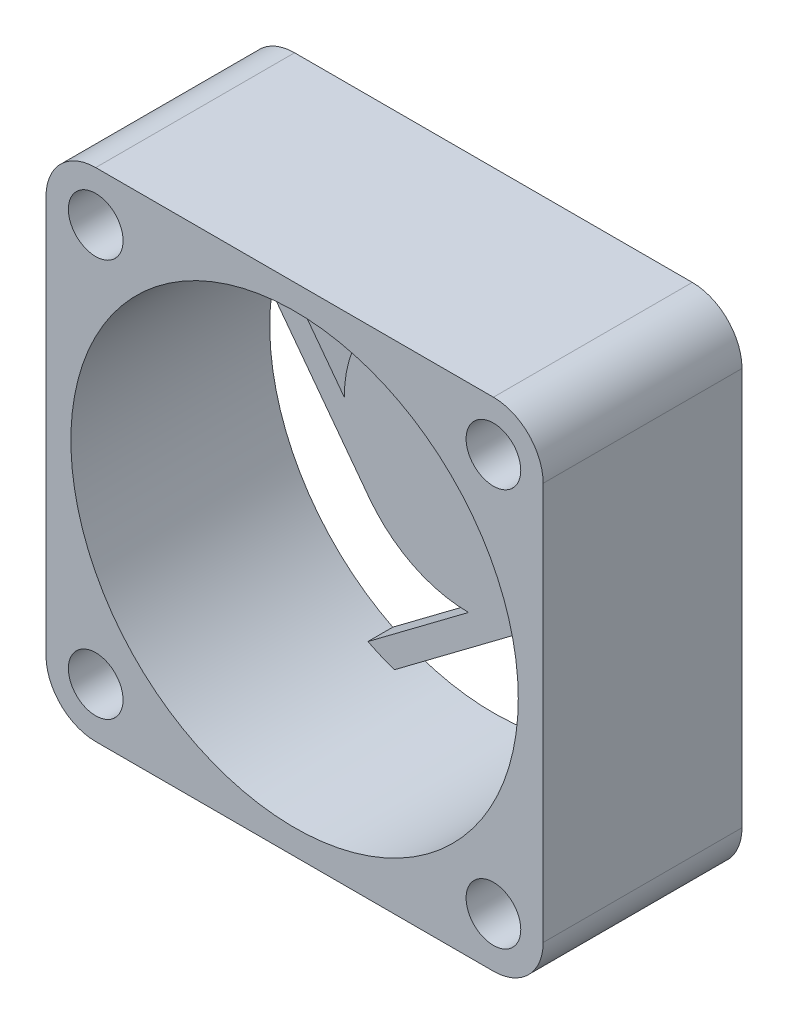
SolidWorks part; units mm, degrees
ref_plane "Front Plane" through (0, 0, 0) normal (0, 0, 1) x (1, 0, 0)
ref_plane "Top Plane" through (0, 0, 0) normal (0, 1, 0) x (1, 0, 0)
ref_plane "Right Plane" through (0, 0, 0) normal (1, 0, 0) x (0, 0, -1)
sketch "Sketch1" plane through (0, 0, 0) normal (0, 0, 1) x (1, 0, 0)
  line L1 (-10, -10) -> (10, -10)
  line L2 (-10, -10) -> (-10, 10)
  line L3 (-10, 10) -> (10, 10)
  line L4 (10, -10) -> (10, 10)
  line L5 (-10, -10) -> (10, 10) construction
  line L6 (-10, 10) -> (10, -10) construction
  circle A0 centre (-8, 8) radius 1.1
  circle A1 centre (-8, -8) radius 1.1
  circle A2 centre (8, -8) radius 1.1
  circle A3 centre (8, 8) radius 1.1
  point P0 (0, 0)
  dimension "D3" = 2.2
  dimension "D1" = 20
  dimension "D2" = 20
  dimension "D4" = 8
  dimension "D5" = 2
  dimension "D6" = 2
extrude "Boss-Extrude1" add sketch "Sketch1" along normal blind 8
sketch "Sketch2" plane through (0, 0, 8) normal (0, 0, 1) x (1, 0, 0)
  circle A0 centre (0, 0) radius 9
  dimension "D1" = 18
extrude "Cut-Extrude1" cut sketch "Sketch2" against normal blind 7
sketch "Sketch3" plane through (0, 0, 1) normal (0, 0, 1) x (1, 0, 0)
  line L0 (3, -4) -> (-2.9867, -8.49)
  line L1 (0, -5) -> (-4.0498, -8.0374)
  line L2 (-5, 0) -> (-8.0374, 4.0498)
  line L3 (-4, -3) -> (-8.49, 2.9867)
  line L4 (0, 5) -> (4.0498, 8.0374)
  line L5 (-3, 4) -> (2.9867, 8.49)
  line L6 (5, 0) -> (8.0374, -4.0498)
  line L7 (4, 3) -> (8.49, -2.9867)
  arc A0 (-8.49, 2.9867) -> (-4.0498, -8.0374) centre (0, 0) ccw
  arc A1 (-4, -3) -> (0, -5) centre (0, 0) ccw
  arc A2 (-8.0374, 4.0498) -> (-8.49, 2.9867) centre (0, 0) ccw construction
  arc A3 (-5, 0) -> (-4, -3) centre (0, 0) ccw construction
  arc A4 (0, 5) -> (-3, 4) centre (0, 0) ccw construction
  arc A5 (-3, 4) -> (-5, 0) centre (0, 0) ccw
  arc A6 (5, 0) -> (4, 3) centre (0, 0) ccw construction
  arc A7 (4, 3) -> (0, 5) centre (0, 0) ccw
  arc A8 (0, -5) -> (3, -4) centre (0, 0) ccw construction
  arc A9 (3, -4) -> (5, 0) centre (0, 0) ccw
  arc A10 (-4.0498, -8.0374) -> (-2.9867, -8.49) centre (0, 0) ccw construction
  arc A11 (-2.9867, -8.49) -> (8.0374, -4.0498) centre (0, 0) ccw
  arc A12 (8.0374, -4.0498) -> (8.49, -2.9867) centre (0, 0) ccw construction
  arc A13 (8.49, -2.9867) -> (4.0498, 8.0374) centre (0, 0) ccw
  arc A14 (4.0498, 8.0374) -> (2.9867, 8.49) centre (0, 0) ccw construction
  arc A15 (2.9867, 8.49) -> (-8.0374, 4.0498) centre (0, 0) ccw
  point P23 (0, 0)
  dimension "D1" = 18
  dimension "D2" = 10
  dimension "D3" = 1
  dimension "D4" = 3
  dimension "D5" = 4
extrude "Cut-Extrude2" cut sketch "Sketch3" against normal up to next
fillet "Fillet1" radius 2 4 edges at (10, -10, 4) (-10, -10, 4) (-10, 10, 4) (10, 10, 4)
